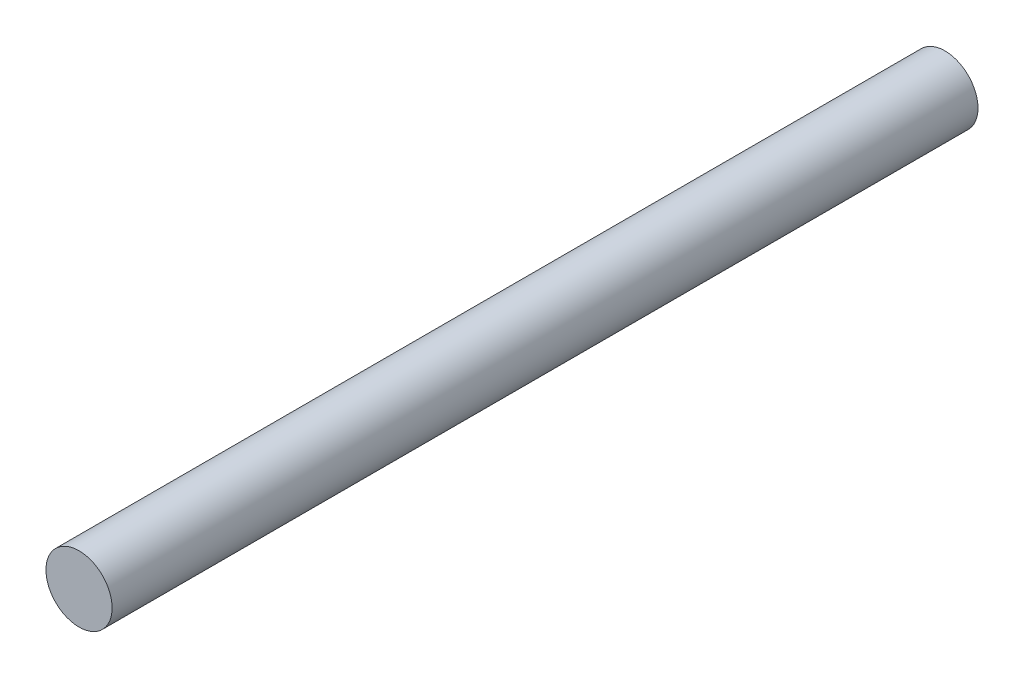
SolidWorks part; units mm, degrees
material "Plain Carbon Steel"
ref_plane "Front Plane" through (0, 0, 0) normal (0, 0, 1) x (1, 0, 0)
ref_plane "Top Plane" through (0, 0, 0) normal (0, 1, 0) x (1, 0, 0)
ref_plane "Right Plane" through (0, 0, 0) normal (1, 0, 0) x (0, 0, -1)
sketch "Sketch1" plane through (0, 0, 0) normal (0, 0, 1) x (1, 0, 0)
  circle A0 centre (0, 0) radius 3
  dimension "D1" = 6
extrude "Boss-Extrude1" add sketch "Sketch1" along normal mid plane 78.5
cosmetic thread "Cosmetic Thread1" parameters "D1"=19, "D2"=4.891
cosmetic thread "Cosmetic Thread2" parameters "D1"=19, "D2"=4.891
